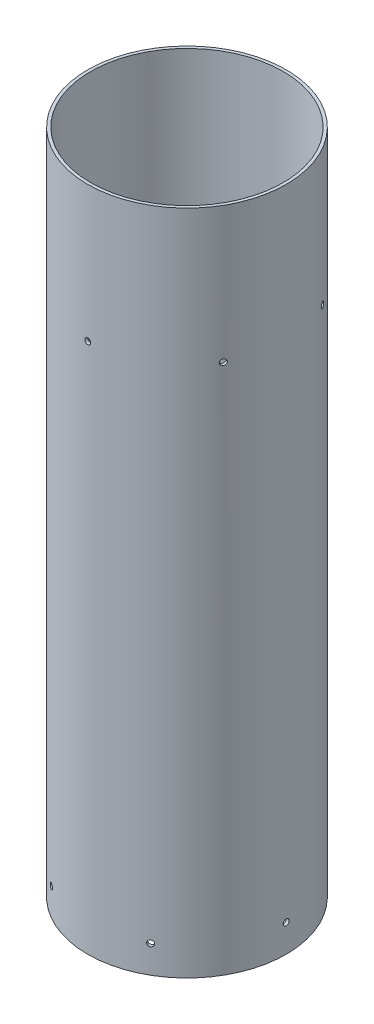
SolidWorks part; units mm, degrees
ref_plane "Front Plane" through (0, 0, 0) normal (0, 0, 1) x (1, 0, 0)
ref_plane "Top Plane" through (0, 0, 0) normal (0, 1, 0) x (1, 0, 0)
ref_plane "Right Plane" through (0, 0, 0) normal (1, 0, 0) x (0, 0, -1)
sketch "Sketch3" plane through (0, 0, 0) normal (0, 1, 0) x (1, 0, 0)
  circle A0 centre (0, 0) radius 51.054
  circle A1 centre (0, 0) radius 49.53
  dimension "D1" = 102.108
  dimension "D2" = 99.06
extrude "Boss-Extrude1" add sketch "Sketch3" along normal blind 342.9
sketch "Sketch4" plane through (0, 0, 0) normal (0, 0, 1) x (1, 0, 0)
  line L0 (0, 342.9) -> (0, 274.574) construction
  line L1 (49.53, 342.9) -> (-49.53, 342.9) construction
  line L2 (0, 274.574) -> (0, 273.05) construction
  circle A0 centre (0, 273.05) radius 1.524
  dimension "D2" = 3.048
  dimension "D1" = 68.326
extrude "Cut-Extrude1" cut sketch "Sketch4" against normal blind 71.12 contours A0
pattern_circular "CirPattern1" count 6 over 360 about axis through (0, 342.9, 0) along (0, -1, 0) of "Cut-Extrude1"
sketch "Sketch5" plane through (0, 0, 0) normal (1, 0, 0) x (0, 0, -1)
  line L0 (0, 0) -> (0, 12.7)
  line L1 (0, 12.7) -> (0, 14.224)
  circle A0 centre (0, 14.224) radius 1.524
  dimension "D2" = 3.048
  dimension "D1" = 12.7
extrude "Cut-Extrude2" cut sketch "Sketch5" against normal blind 177.8
pattern_circular "CirPattern2" count 6 over 360 about axis through (0, 342.9, 0) along (0, -1, 0) of "Cut-Extrude2"
